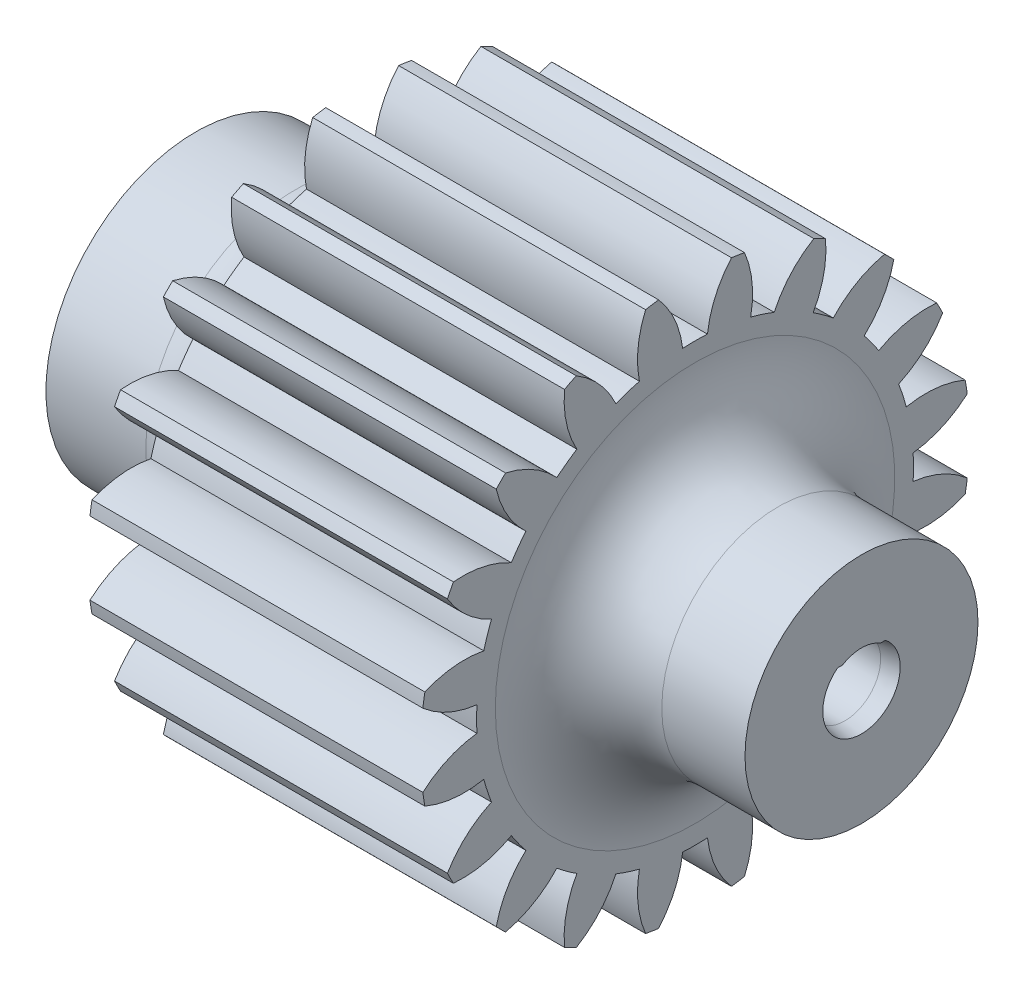
SolidWorks part; units mm, degrees
ref_plane "Plane1" through (0, 0, 0) normal (0, 0, 1) x (1, 0, 0)
ref_plane "Plane2" through (0, 0, 0) normal (0, 1, 0) x (1, 0, 0)
ref_plane "Plane3" through (0, 0, 0) normal (1, 0, 0) x (0, 0, -1)
other "Configuration Table"
sketch "HoldingSke" plane through (0, 0, 0) normal (0, 1, 0) x (1, 0, 0)
  line L0 (0, 0) -> (0.6265, -0.228)
  line L1 (-15, 0) -> (100, 0) construction
  line L2 (0, 0) -> (-2.1039, 2.3779)
  line L3 (0, 0) -> (-11.863, 4.5341)
  line L4 (0, 0) -> (8.1152, 2.9537)
  line L5 (0, 0) -> (-46.8476, -17.4728)
  line L6 (0, 0) -> (-16.5793, -11.1861)
  line L7 (-2.1039, 2.3779) -> (8.6586, 51.2059)
  line L8 (-76.2, 54.61) -> (-75.5, 54.61)
  line L9 (-71.009, 38.7566) -> (-53.1078, 45.2721)
  line L10 (-76.2, 71.12) -> (104.1128, 71.12)
  line L11 (0, 0) -> (-20, 0)
  line L12 (-76.2, 101.6) -> (-76.147, 101.6)
  line L13 (24.9733, 27.94) -> (52.9518, 28.4284)
  line L14 (24.9733, 27.94) -> (24.9743, 27.94)
  line L15 (24.9733, 27.94) -> (100.4006, 29.5858)
  line L16 (-63.627, -1.5) -> (-12.827, -1.5)
  circle A0 centre (0, 0) radius 2
  circle A1 centre (0, 0) radius 13.124
  circle A2 centre (0, 0) radius 37.5
  circle A3 centre (0, 0) radius 2
  dimension "MHD" = 26.248
  dimension "Hub_dia" = 75
  dimension "Bore" = 4
  dimension "MBD" = 4
  dimension "Num_teeth" = 20
  dimension "Pitch" = 0.6667
  dimension "Overall_len" = 50
  dimension "Show_teeth" = 20
  dimension "Thickness" = 20
  dimension "OAL" = 50.0001
  dimension "T_dim" = 0.7
  dimension "Ap" = 20
  dimension "H" = 19.05
  dimension "Pitch_radius" = 180.3128
  dimension "Width" = 20
  dimension "Backlash" = 0.053
  dimension "Addendum_fac" = 1
  dimension "Dedendum_fac" = 1.25
  dimension "Clearance_fac" = 0.25
  dimension "Dedendum_add" = 0.001
  dimension "Module" = 1.5
sketch "BasProSke" plane through (0, 0, 0) normal (0, 1, 0) x (1, 0, 0)
  line L0 (-10, 0) -> (60, 0) construction
  line L1 (0, 0) -> (0, 16.5)
  line L2 (0, 0) -> (20, 0)
  line L3 (20, 0) -> (20, 16.5)
  line L4 (20, 16.5) -> (0, 16.5)
  dimension "Thickness" = 20
  dimension "Diameter" = 33
revolve "Base-Revolve" add sketch "BasProSke" angle 360 about L0
sketch "TooCutSke" plane through (0, 0, 0) normal (1, 0, 0) x (0, 0, -1)
  line L1 (0, 0) -> (0, 107) construction
  line L2 (0, 0) -> (-1.2696, 14.9462) construction
  line L3 (0, 0) -> (-4.6808, 29.5532) construction
  line L4 (-1.2696, 14.9462) -> (-2.3404, 14.7766) construction
  arc A0 (0.7438, 13.1029) -> (-0.7438, 13.1029) centre (0, 0) ccw
  arc A1 (2.21, 16.377) -> (-2.21, 16.377) centre (0, 0) ccw
  circle A2 centre (0, 0) radius 15 construction
  circle A3 centre (0, 0) radius 14.0954 construction
  arc A4 (-0.7438, 13.1029) -> (-2.21, 16.377) centre (-6.7025, 12.3999) ccw
  arc A5 (2.21, 16.377) -> (0.7438, 13.1029) centre (6.7025, 12.3999) ccw
  dimension "Root_dia" = 26.248
  dimension "Overcut_dia" = 33.0508
  dimension "Pitch_dia" = 30
  dimension "Base_dia" = 28.1908
  dimension "Flank_rad" = 6
  dimension "Half_ang" = 9
  dimension "Half_CT" = 1.0841
extrude "ToothCut" cut sketch "TooCutSke" along normal through all
fillet "Breaks" [suppressed] radius 0.03
fillet "RootFillets" [suppressed] radius 0.376
pattern_circular "TeethCuts" count 20 every 18 about axis through (-10, 0, 0) along (1, 0, 0) of "ToothCut", "RootFillets", "Breaks"
sketch "HubNeaOneSke" plane through (0, 0, 0) normal (-1, 0, 0) x (0, 0, 1)
  circle A0 centre (0, 0) radius 13.124
  dimension "Diameter" = 26.248
extrude "HubNearOne" [suppressed] add sketch "HubNeaOneSke" along normal blind 30.0001
sketch "HubNeaBotSke" plane through (0, 0, 0) normal (-1, 0, 0) x (0, 0, 1)
  circle A0 centre (0, 0) radius 13.124
  dimension "Diameter" = 26.248
extrude "HubNearBoth" [suppressed] add sketch "HubNeaBotSke" along normal blind 15
ref_plane "FarPln" through (20, 0, 0) normal (1, 0, 0) x (0, 0, -1)
sketch "HubFarSke" plane through (20, 0, 0) normal (1, 0, 0) x (0, 0, -1)
  circle A0 centre (0, 0) radius 13.124
  dimension "Diameter" = 26.248
extrude "HubFar" [suppressed] add sketch "HubFarSke" along normal blind 15
sketch "BorSke" plane through (0, 0, 0) normal (1, 0, 0) x (0, 0, -1)
  circle A0 centre (0, 0) radius 0.5
  dimension "Diameter" = 1
extrude "Bore" cut sketch "BorSke" along normal mid plane 100.0001
sketch "KeySke" plane through (0, 0, 0) normal (1, 0, 0) x (0, 0, -1)
  line L0 (-0.8, 0) -> (-0.8, 2.7)
  line L1 (-0.8, 2.7) -> (0.8, 2.7)
  line L2 (0.8, 2.7) -> (0.8, 0)
  line L3 (0, 0) -> (0, 34) construction
  line L4 (-0.8, 0) -> (0.8, 0)
  dimension "Offset" = 2.7
  dimension "Width" = 1.6
extrude "Keyway" [suppressed] cut sketch "KeySke" along normal mid plane 100.0001
pattern_circular "Keyway2" [suppressed] count 2 every 90 about axis through (-10, 0, 0) along (1, 0, 0)
sketch "Sketch1" plane through (20, 0, 0) normal (1, 0, 0) x (0, 0, -1)
  circle A0 centre (0, 0) radius 7
  circle A1 centre (0, 0) radius 0.5
  circle A2 centre (0, 0) radius 0.5 construction
  dimension "D1" = 14
extrude "Boss-Extrude1" add sketch "Sketch1" along normal blind 10
fillet "Fillet1" radius 5 1 edges at (20, 0, 7)
sketch "Sketch2" plane through (0, 0, 0) normal (-1, 0, 0) x (0, 0, 1)
  circle A0 centre (0, 0) radius 9
  dimension "D1" = 18
extrude "Boss-Extrude2" add sketch "Sketch2" along normal up to surface (10 mm away)
sketch "Sketch3" plane through (-10, 0, 0) normal (-1, 0, 0) x (0, 0, 1)
  circle A0 centre (0, 0) radius 3
  dimension "D1" = 6
extrude "Boss-Extrude3" add sketch "Sketch3" along normal up to surface (3.2 mm away)
fillet "Fillet2" radius 4 1 edges at (0, 0, -9)
sketch "Sketch4" plane through (30, 0, 0) normal (1, 0, 0) x (0, 0, -1)
  line L0 (-1.3229, 1.5) -> (1.3229, 1.5) construction
  line L1 (-1.3784, 1.65) -> (1.3784, 1.65)
  arc A2 (-1.3229, 1.5) -> (1.3229, 1.5) centre (0, 0) ccw construction
  arc A3 (-1.3784, 1.65) -> (1.3784, 1.65) centre (0, 0) ccw
  point P4 (0, -2)
  dimension "D1" = 4
  dimension "D2" = 3.5
  dimension "D3" = 0.15
extrude "Cut-Extrude1" cut sketch "Sketch4" against normal blind 25 contours A3 L1
chamfer "Chamfer2" distance 1 angle 10 2 edges at (30, -2.15, 0) (30, 1.65, 0)
sketch "Sketch5" plane through (30, 0, 0) normal (1, 0, 0) x (0, 0, -1)
  circle A0 centre (0, 0) radius 2.15
extrude "Cut-Extrude2" cut sketch "Sketch5" against normal blind 3
equation "' \"Module@HoldingSke\" = 6.35"
equation "' \"Num_teeth@HoldingSke\" = 12"
equation "' \"Ap@HoldingSke\" =  20"
equation "' \"Ap@HoldingSke\" = 20"
equation "' \"Width@HoldingSke\" = 0.5 * 25.4"
equation "' \"Hub_dia@HoldingSke\"= 1 * 25.4"
equation "' \"Hub_dia@HoldingSke\" = 1 * 25.4"
equation "' \"Overall_len@HoldingSke\" = 1.0 * 25.4"
equation "' \"Bore@HoldingSke\" = 0.75 * 25.4"
equation "' \"T_dim@HoldingSke\" = 0.1 * 25.4"
equation "' \"Width@KeySke\" = 0.25 * 25.4"
equation "' \"Show_teeth@HoldingSke\" = 13"
equation "' \"Backlash@HoldingSke\" = 0.009 * 25.4"
equation "' \"Addendum_fac@HoldingSke\" = 1.0"
equation "' \"Dedendum_fac@HoldingSke\" = 1.25"
equation "' \"Dedendum_add@HoldingSke\" = 0.00005 * 25.4"
equation "' \"Clearance_fac@HoldingSke\" = 0.25"
equation "\"Pitch@HoldingSke\" = 1 / \"Module@HoldingSke\""
equation "\"Overcut_dia@TooCutSke\" = (\"Num_teeth@HoldingSke\" + 2 * \"Addendum_fac@HoldingSke\") / \"Pitch@HoldingSke\" + 0.002 * 25.4"
equation "\"Pitch_dia@TooCutSke\" = \"Num_teeth@HoldingSke\" / \"Pitch@HoldingSke\""
equation "\"Base_dia@TooCutSke\" = \"Num_teeth@HoldingSke\" / \"Pitch@HoldingSke\" * cos((\"Ap@HoldingSke\"  * 3.14159265 / 180))"
equation "\"Root_dia@TooCutSke\" = (\"Num_teeth@HoldingSke\" + 2) / \"Pitch@HoldingSke\" - 2 * (\"Addendum_fac@HoldingSke\" + \"Dedendum_fac@HoldingSke\") / \"Pitch@HoldingSke\" - \"Dedendum_add@HoldingSke\" * 2"
equation "\"Half_ang@TooCutSke\" = 180 / \"Num_teeth@HoldingSke\""
equation "\"Half_CT@TooCutSke\" = \"Num_teeth@HoldingSke\" / \"Pitch@HoldingSke\" * sin((3.14159265 / 2 / \"Num_teeth@HoldingSke\")) / 2 - 7 * \"Backlash@HoldingSke\" / 4"
equation "\"Flank_rad@TooCutSke\" = \"Num_teeth@HoldingSke\" / \"Pitch@HoldingSke\" / 5"
equation "\"Radius@RootFillets\" = \"Clearance_fac@HoldingSke\" / \"Pitch@HoldingSke\" + \"Dedendum_add@HoldingSke\""
equation "\"Break_rad@Breaks\" = 0.02 / \"Pitch@HoldingSke\""
equation "\"Thickness@HoldingSke\" = \"Width@HoldingSke\""
equation "\"OAL@HoldingSke\" = \"Thickness@HoldingSke\""
equation "\"MHD@HoldingSke\" = (\"Num_teeth@HoldingSke\" + 2) / \"Pitch@HoldingSke\" - 2 * (\"Addendum_fac@HoldingSke\" + \"Dedendum_fac@HoldingSke\")  / \"Pitch@HoldingSke\" - \"Dedendum_add@HoldingSke\" * 2"
equation "\"MBD@HoldingSke\" = (\"Num_teeth@HoldingSke\" + 2) / \"Pitch@HoldingSke\" - 2 * (\"Addendum_fac@HoldingSke\" + \"Dedendum_fac@HoldingSke\")  / \"Pitch@HoldingSke\" - \"Dedendum_add@HoldingSke\" * 2 - 0.002 * 25.4"
equation "\"MHD@HoldingSke\" = ((sgn( \"MHD@HoldingSke\" - \"Hub_dia@HoldingSke\" )-1)*( \"MHD@HoldingSke\" - \"Hub_dia@HoldingSke\" ))/-2+ \"Hub_dia@HoldingSke\""
equation "\"MBD@HoldingSke\" = ((sgn( \"MBD@HoldingSke\" - \"Bore@HoldingSke\" )-1)*( \"MBD@HoldingSke\" - \"Bore@HoldingSke\" ))/-2+ \"Bore@HoldingSke\""
equation "\"OAL@HoldingSke\" = ((sgn( \"OAL@HoldingSke\" - \"Overall_len@HoldingSke\" )+1)*( \"OAL@HoldingSke\" - \"Overall_len@HoldingSke\" ))/2 + \"Overall_len@HoldingSke\" + 0.000002 * 25.4"
equation "\"Num_teeth@TeethCuts\" = int( \"Show_teeth@HoldingSke\" ) + 1"
equation "\"Num_teeth@TeethCuts\" = ((sgn( \"Num_teeth@TeethCuts\" - \"Num_teeth@HoldingSke\" )-1)*( \"Num_teeth@TeethCuts\" - \"Num_teeth@HoldingSke\" ))/-2+ \"Num_teeth@HoldingSke\""
equation "\"Num_teeth@TeethCuts\" = ((sgn( \"Num_teeth@TeethCuts\" - 2.0)+1)*( \"Num_teeth@TeethCuts\" - 2.0))/2 +2.0"
equation "\"Angle@TeethCuts\" = 360.0 / \"Num_teeth@HoldingSke\""
equation "\"Diameter@BasProSke\" = (\"Num_teeth@HoldingSke\" + 2 * \"Addendum_fac@HoldingSke\") / \"Pitch@HoldingSke\""
equation "\"Thickness@BasProSke\"  = \"Thickness@HoldingSke\""
equation "' \"Fillet_rad@BasProSke\" =  \"Thickness@HoldingSke\" * 0.05"
equation "' \"Fillet_rad@BasProSke\" = \"Thickness@HoldingSke\" * 0.05"
equation "\"MHD@HoldingSke\" = ((sgn( \"MHD@HoldingSke\" - \"Root_dia@TooCutSke\" )-1)*( \"MHD@HoldingSke\" - \"Root_dia@TooCutSke\" ))/-2+ \"Root_dia@TooCutSke\""
equation "\"Diameter@HubNeaOneSke\" = \"MHD@HoldingSke\""
equation "\"Length@HubNearOne\" = \"OAL@HoldingSke\" - \"Thickness@BasProSke\""
equation "\"Diameter@HubNeaBotSke\" = \"MHD@HoldingSke\""
equation "\"Length@HubNearBoth\" = ( \"OAL@HoldingSke\" - \"Thickness@BasProSke\" ) / 2.0"
equation "\"Thickness@FarPln\" = \"Thickness@BasProSke\""
equation "\"Diameter@HubFarSke\" = \"MHD@HoldingSke\""
equation "\"Length@HubFar\" = ( \"OAL@HoldingSke\" - \"Thickness@BasProSke\" ) / 2.0"
equation "\"D1@Bore\" = \"OAL@HoldingSke\" * 2.0"
equation "\"D1@Keyway\" = \"OAL@HoldingSke\" * 2.0"
equation "\"Offset@KeySke\" = \"T_dim@HoldingSke\" + \"MBD@HoldingSke\" / 2.0"
